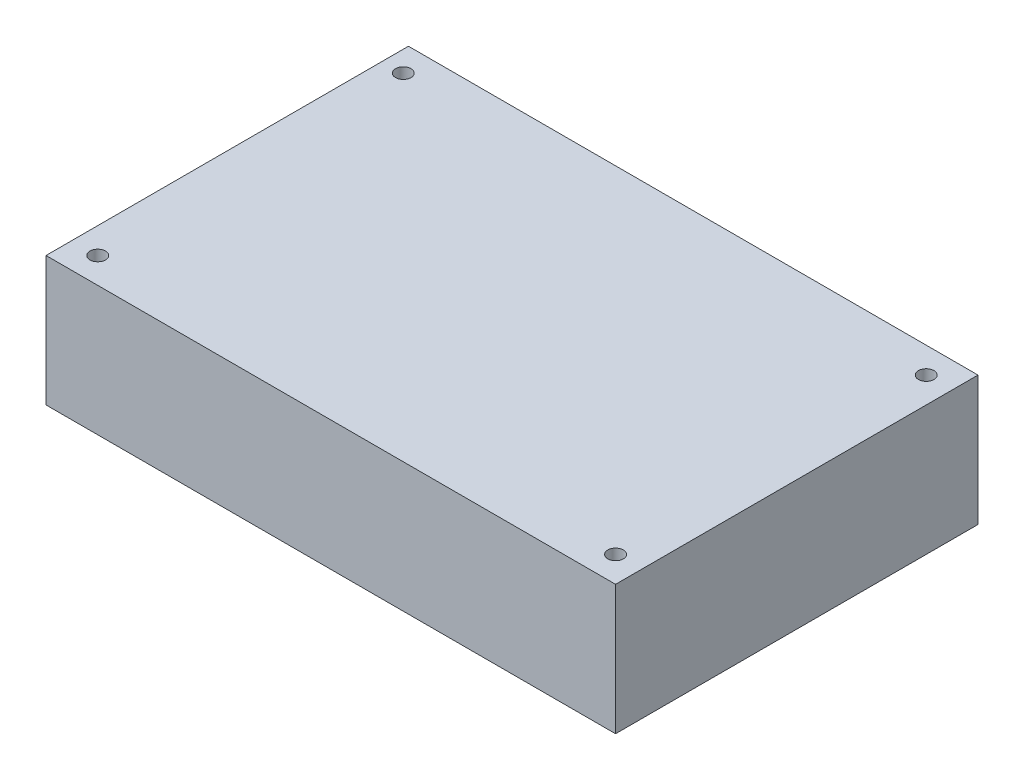
SolidWorks part; units mm, degrees
ref_plane "Front Plane" through (0, 0, 0) normal (0, 0, 1) x (1, 0, 0)
ref_plane "Top Plane" through (0, 0, 0) normal (0, 1, 0) x (1, 0, 0)
ref_plane "Right Plane" through (0, 0, 0) normal (1, 0, 0) x (0, 0, -1)
sketch "Sketch1" plane through (0, 0, 0) normal (0, 1, 0) x (1, 0, 0)
  line L1 (-55, -35) -> (55, -35)
  line L2 (-55, -35) -> (-55, 35)
  line L3 (-55, 35) -> (55, 35)
  line L4 (55, -35) -> (55, 35)
  line L5 (-55, -35) -> (55, 35) construction
  line L6 (-55, 35) -> (55, -35) construction
  circle A0 centre (-51, 30) radius 1.5
  circle A1 centre (50, 30) radius 1.5
  circle A2 centre (50, -30) radius 1.5
  circle A3 centre (-50, -30) radius 1.5
  point P0 (0, 0)
  point P14 (0, 0)
  dimension "D3" = 3
  dimension "D4" = 3
  dimension "D5" = 3
  dimension "D6" = 3
  dimension "D1" = 110
  dimension "D2" = 70
  dimension "D7" = 5
  dimension "D8" = 4
  dimension "D9" = 5
  dimension "D10" = 5
  dimension "D11" = 5
  dimension "D12" = 5
  dimension "D13" = 5
  dimension "D14" = 5
extrude "Boss-Extrude1" add sketch "Sketch1" along normal blind 25
